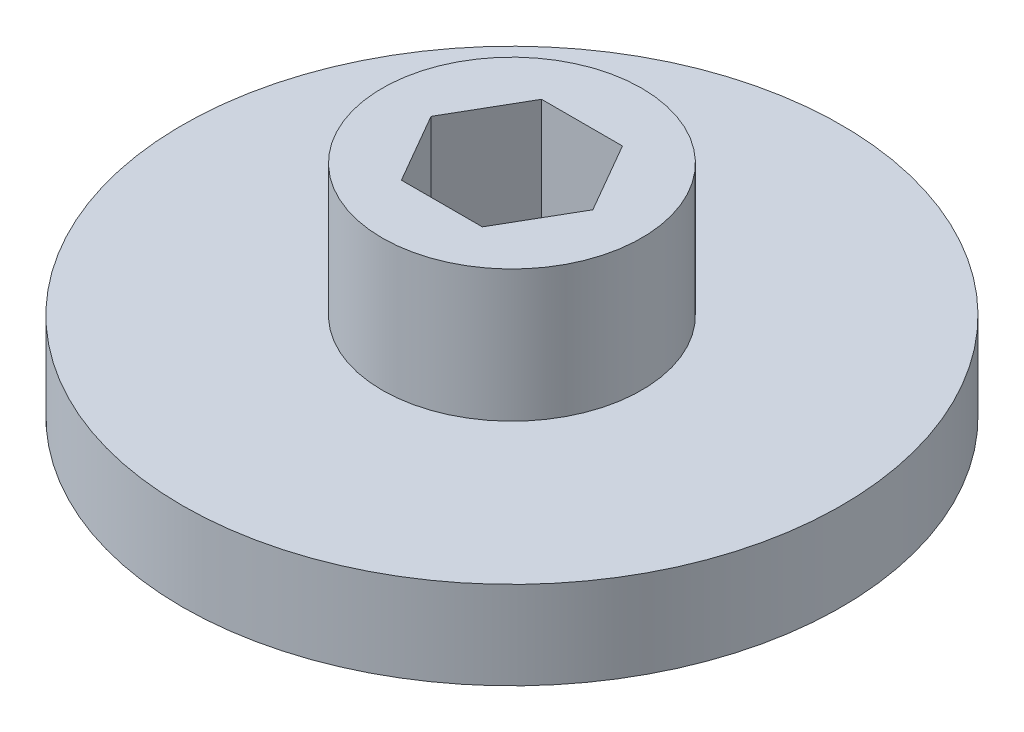
SolidWorks part; units mm, degrees
ref_plane "Front Plane" through (0, 0, 0) normal (0, 0, 1) x (1, 0, 0)
ref_plane "Top Plane" through (0, 0, 0) normal (0, 1, 0) x (1, 0, 0)
ref_plane "Right Plane" through (0, 0, 0) normal (1, 0, 0) x (0, 0, -1)
sketch "Sketch1" plane through (0, 0, 0) normal (0, 1, 0) x (1, 0, 0)
  circle A0 centre (0, 0) radius 19.05
  dimension "D1" = 38.1
extrude "Boss-Extrude1" add sketch "Sketch1" along normal blind 5.08
sketch "Sketch3" plane through (0, 5.08, 0) normal (0, 1, 0) x (1, 0, 0)
  circle A0 centre (0, 0) radius 7.5
  dimension "D1" = 15
extrude "Boss-Extrude2" add sketch "Sketch3" along normal blind 7.62
sketch "Sketch4" plane through (0, 12.7, 0) normal (0, 1, 0) x (1, 0, 0)
  line L0 (-6.985, 0) -> (6.985, 0) construction
  line L1 (4.6765, 0) -> (2.3383, 4.05)
  line L2 (2.3383, 4.05) -> (-2.3383, 4.05)
  line L3 (-2.3383, 4.05) -> (-4.6765, 0)
  line L4 (-4.6765, 0) -> (-2.3383, -4.05)
  line L5 (-2.3383, -4.05) -> (2.3383, -4.05)
  line L6 (2.3383, -4.05) -> (4.6765, 0)
  circle A0 centre (0, 0) radius 4.05 construction
  dimension "D1" = 8.1
extrude "Cut-Extrude1" cut sketch "Sketch4" against normal up to surface (7.62 mm away) up to face at (0, 5.08, 7.5)
sketch "Sketch5" plane through (0, 0, 0) normal (0, -1, 0) x (1, 0, 0)
  circle A0 centre (0, 0) radius 15.494
  dimension "D1" = 30.988
extrude "Cut-Extrude2" cut sketch "Sketch5" against normal blind 3.81
